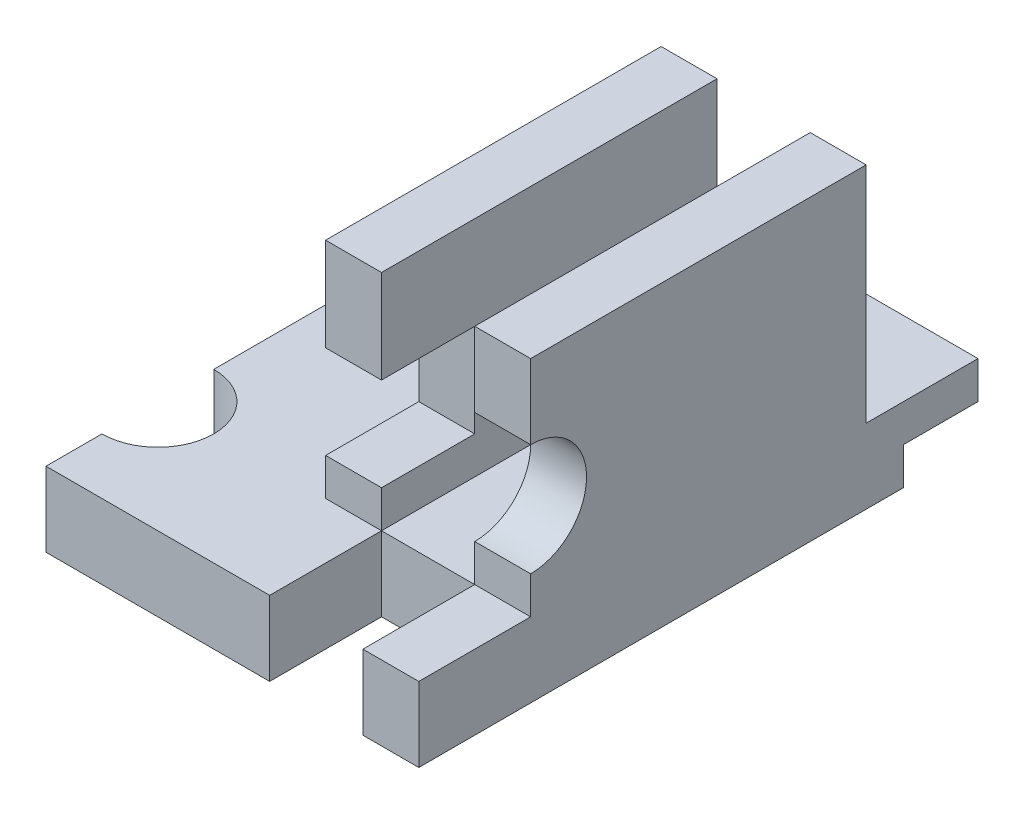
SolidWorks part; units mm, degrees
ref_plane "Спереди" through (0, 0, 0) normal (0, 0, 1) x (1, 0, 0)
ref_plane "Сверху" through (0, 0, 0) normal (0, 1, 0) x (1, 0, 0)
ref_plane "Справа" through (0, 0, 0) normal (1, 0, 0) x (0, 0, -1)
sketch "Эскиз1" plane through (0, 0, 0) normal (0, 1, 0) x (1, 0, 0)
  line L1 (-50, -75) -> (50, -75)
  line L2 (-50, -75) -> (-50, 75)
  line L3 (-50, 75) -> (50, 75)
  line L4 (50, -75) -> (50, 75)
  line L5 (-50, -75) -> (50, 75) construction
  line L6 (-50, 75) -> (50, -75) construction
  point P0 (0, 0)
  dimension "D1" = 100
  dimension "D2" = 150
extrude "Бобышка-Вытянуть1" add sketch "Эскиз1" against normal blind 20
sketch "Эскиз2" plane through (0, 0, 0) normal (0, 1, 0) x (1, 0, 0)
  line L0 (-50, 75) -> (-50, -75) construction
  circle A0 centre (-50, -45) radius 15
  dimension "D2" = 30
  dimension "D1" = 30
extrude "Вырез-Вытянуть1" cut sketch "Эскиз2" against normal blind 20 contours A0
sketch "Эскиз3" plane through (0, 0, 0) normal (0, 1, 0) x (1, 0, 0)
  line L0 (10, -75) -> (10, -45)
  line L1 (-50, -75) -> (50, -75) construction
  line L2 (10, -45) -> (35, -45)
  line L3 (35, -45) -> (35, -75)
  line L4 (10, -75) -> (35, -75)
  dimension "D1" = 25
  dimension "D2" = 30
  dimension "D3" = 15
extrude "Вырез-Вытянуть2" cut sketch "Эскиз3" against normal blind 20 contours L3 L4 L0 L2
sketch "Эскиз4" plane through (0, 0, 0) normal (0, 1, 0) x (1, 0, 0)
  line L4 (10, -45) -> (35, -45) construction
  line L5 (-5, -45) -> (-5, 45)
  line L6 (-5, 45) -> (10, 45)
  line L8 (10, -45) -> (10, 45)
  line L10 (10, -45) -> (-5, -45)
  dimension "D1" = 15
  dimension "D2" = 90
extrude "Бобышка-Вытянуть2" add sketch "Эскиз4" along normal blind 60
sketch "Эскиз5" plane through (0, 0, 0) normal (0, 1, 0) x (1, 0, 0)
  line L0 (22.5, -45) -> (22.5, 75) construction
  line L1 (10, -45) -> (35, -45) construction
  line L2 (50, 75) -> (-50, 75) construction
sketch "Эскиз6" plane through (0, 0, 0) normal (0, 1, 0) x (1, 0, 0)
  line L0 (35, -45) -> (50, -45)
  line L1 (50, -75) -> (50, 75) construction
  line L2 (50, -45) -> (50, 45)
  line L3 (50, 45) -> (35, 45)
  line L4 (35, 45) -> (35, -45)
  line L5 (10, 45) -> (-5, 45) construction
extrude "Бобышка-Вытянуть3" add sketch "Эскиз6" along normal blind 60 contours L4 L0 L2 L3
sketch "Эскиз7" plane through (50, 0, 0) normal (1, 0, 0) x (0, 0, -1)
  line L0 (-45, 60) -> (-45, 0) construction
  line L1 (-45, 40) -> (-45, 10)
  arc A0 (-45, 10) -> (-45, 40) centre (-45, 25) ccw
  dimension "D1" = 30
  dimension "D2" = 10
extrude "Вырез-Вытянуть3" cut sketch "Эскиз7" against normal up to next contours A0 L1
sketch "Эскиз9" plane through (-5, 0, 0) normal (-1, 0, 0) x (0, 0, 1)
  line L0 (45, 10) -> (20, 10)
  line L1 (45, 60) -> (45, 0) construction
  line L2 (20, 10) -> (20, 35)
  line L3 (20, 35) -> (45, 35)
  line L4 (45, 10) -> (45, 35)
  point P7 (44.5451, 11.2606)
  dimension "D1" = 25
  dimension "D2" = 25
  dimension "D3" = 10
extrude "Вырез-Вытянуть4" cut sketch "Эскиз9" against normal up to next contours L0 L2 L3 L4
sketch "Эскиз10" plane through (50, 0, 0) normal (1, 0, 0) x (0, 0, -1)
  line L0 (75, -10) -> (55, -10)
  line L1 (75, -20) -> (75, 0) construction
  line L2 (55, -10) -> (55, -20)
  line L3 (-75, -20) -> (75, -20) construction
  line L4 (55, -20) -> (75, -20)
  line L5 (75, -20) -> (75, -10)
  dimension "D1" = 20
extrude "Вырез-Вытянуть5" cut sketch "Эскиз10" against normal through all contours L5 L0 L2 L4
